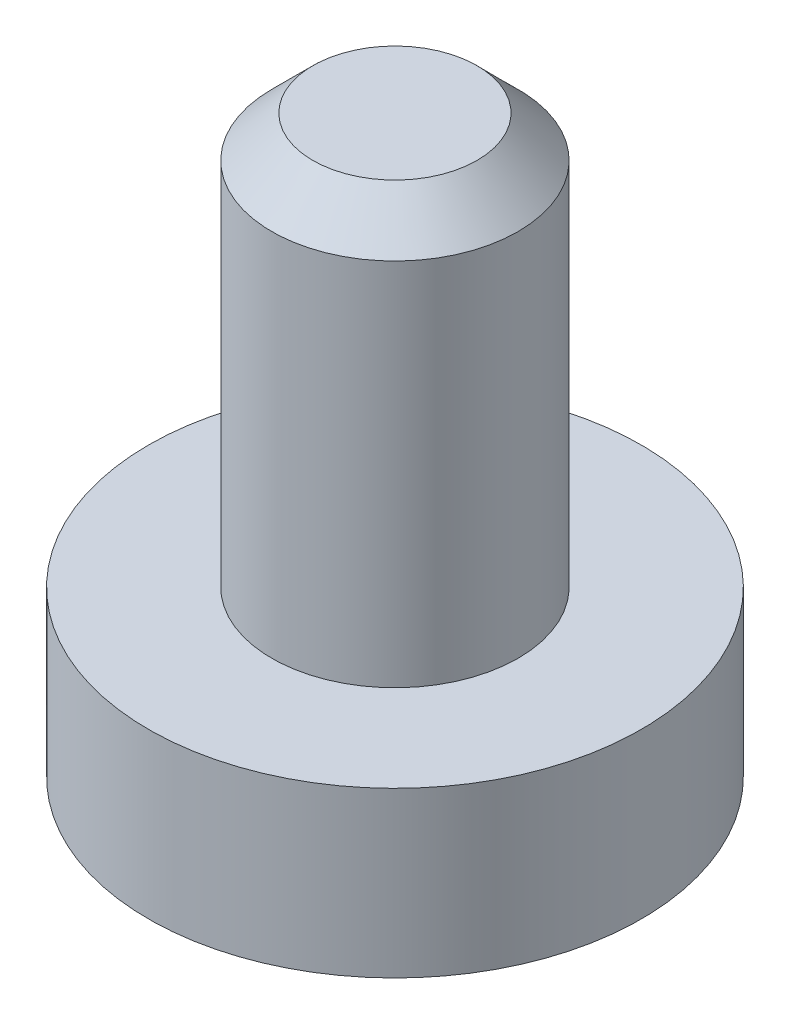
SolidWorks part; units mm, degrees
ref_plane "Front Plane" through (0, 0, 0) normal (0, 0, 1) x (1, 0, 0)
ref_plane "Top Plane" through (0, 0, 0) normal (0, 1, 0) x (1, 0, 0)
ref_plane "Right Plane" through (0, 0, 0) normal (1, 0, 0) x (0, 0, -1)
sketch "Sketch1" plane through (0, 0, 0) normal (0, 0, 1) x (1, 0, 0)
  line L0 (0, 0) -> (3, 0)
  line L1 (3, 0) -> (3, 2)
  line L2 (3, 2) -> (1.5, 2)
  line L3 (1.5, 2) -> (1.5, 7)
  line L4 (1.5, 7) -> (0, 7)
  line L5 (0, 7) -> (0, 0)
  dimension "D1" = 7
  dimension "D2" = 3
  dimension "D3" = 2
  dimension "D4" = 1.5
revolve "Revolve1" add sketch "Sketch1" angle 360 about L5
chamfer "Chamfer1" distance 0.5 angle 45 1 edges at (-1.5, 7, 0)
